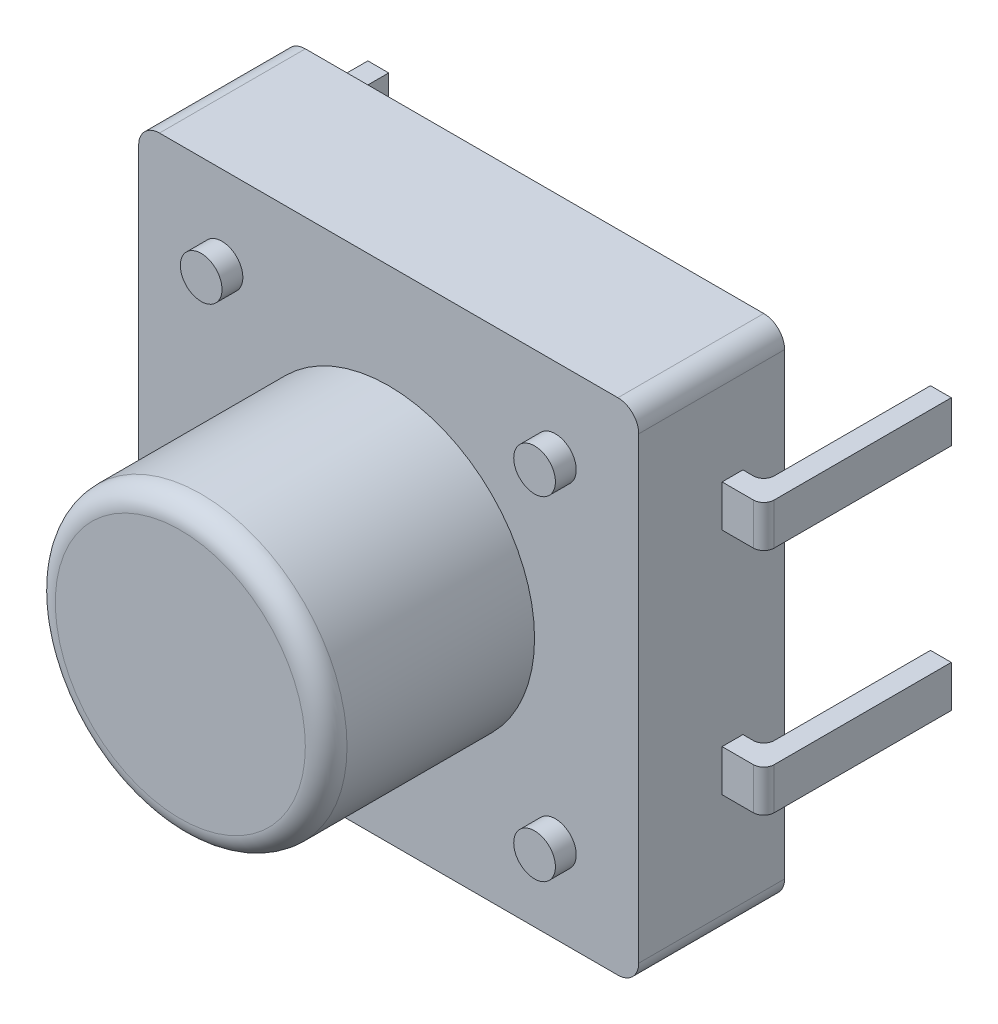
SolidWorks part; units mm, degrees
ref_plane "Ön Düzlem" through (0, 0, 0) normal (0, 0, 1) x (1, 0, 0)
ref_plane "Üst Düzlem" through (0, 0, 0) normal (0, 1, 0) x (1, 0, 0)
ref_plane "Sağ Düzlem" through (0, 0, 0) normal (1, 0, 0) x (0, 0, -1)
sketch "Çizim1" plane through (0, 0, 0) normal (0, 0, 1) x (1, 0, 0)
  line L1 (0.5, 0) -> (11.5, 0)
  line L2 (0, 0.5) -> (0, 11.5)
  line L3 (0.5, 12) -> (11.5, 12)
  line L4 (12, 0.5) -> (12, 11.5)
  arc A0 (0.5, 0) -> (0, 0.5) centre (0.5, 0.5) cw
  arc A1 (12, 0.5) -> (11.5, 0) centre (11.5, 0.5) cw
  arc A2 (12, 11.5) -> (11.5, 12) centre (11.5, 11.5) ccw
  arc A3 (0, 11.5) -> (0.5, 12) centre (0.5, 11.5) cw
  point P7 (0, 0)
  point P10 (12, 0)
  point P13 (12, 12)
  point P16 (0, 12)
  dimension "D3" = 0.5
  dimension "D1" = 12
  dimension "D2" = 12
extrude "Yükseklik-Ekstrüzyon1" add sketch "Çizim1" along normal blind 3.5
sketch "Çizim2" plane through (0, 0, 3.5) normal (0, 0, 1) x (1, 0, 0)
  line L0 (11.8536, 11.8536) -> (0.1464, 0.1464) construction
  line L1 (0.1464, 11.8536) -> (11.8536, 0.1464) construction
  arc A0 (12, 11.5) -> (11.5, 12) centre (11.5, 11.5) ccw construction
  arc A1 (0, 0.5) -> (0.5, 0) centre (0.5, 0.5) ccw construction
  arc A2 (0.5, 12) -> (0, 11.5) centre (0.5, 11.5) ccw construction
  arc A3 (11.5, 0) -> (12, 0.5) centre (11.5, 0.5) ccw construction
  circle A4 centre (6, 6) radius 3.5
  circle A5 centre (10, 10) radius 0.5
  circle A6 centre (2, 10) radius 0.5
  circle A7 centre (2, 2) radius 0.5
  circle A8 centre (10, 2) radius 0.5
  dimension "D1" = 7
  dimension "D2" = 1
  dimension "D3" = 8
extrude "Yükseklik-Ekstrüzyon2" add sketch "Çizim2" along normal blind 0.5
sketch "Çizim3" plane through (0, 0, 4) normal (0, 0, 1) x (1, 0, 0)
  circle A1 centre (6, 6) radius 3.5
  circle A2 centre (6, 6) radius 3.5
  dimension "D1" = 0
extrude "Yükseklik-Ekstrüzyon3" add sketch "Çizim3" along normal blind 4.5
ref_plane "Düzlem1" through (0, 3, 0) normal (0, -1, 0) x (-1, 0, 0)
sketch "Çizim4" plane through (0, 3, 0) normal (0, -1, 0) x (-1, 0, 0)
  line L0 (0, -1) -> (0.25, -1)
  line L1 (0, -3.5) -> (0, 0) construction
  line L2 (0.5, -0.75) -> (0.5, 3)
  line L3 (0.5, 3) -> (1, 3)
  line L4 (1, 3) -> (1, -1.25)
  line L5 (0.75, -1.5) -> (0, -1.5)
  line L6 (0, -1.5) -> (0, -1)
  line L7 (0, 0) -> (-0.5, 0) construction
  line L8 (-6, 0) -> (-6, -3.5) construction
  line L9 (-0.5, 0) -> (-11.5, 0) construction
  line L10 (-0.5, -3.5) -> (-11.5, -3.5) construction
  line L11 (-12, -1.5) -> (-12, -1)
  line L12 (-12.75, -1.5) -> (-12, -1.5)
  line L13 (-13, 3) -> (-13, -1.25)
  line L14 (-12.5, 3) -> (-13, 3)
  line L15 (-12.5, -0.75) -> (-12.5, 3)
  line L16 (-12, -1) -> (-12.25, -1)
  arc A0 (0.5, -0.75) -> (0.25, -1) centre (0.25, -0.75) cw
  arc A1 (1, -1.25) -> (0.75, -1.5) centre (0.75, -1.25) cw
  arc A2 (-13, -1.25) -> (-12.75, -1.5) centre (-12.75, -1.25) ccw
  arc A3 (-12.5, -0.75) -> (-12.25, -1) centre (-12.25, -0.75) ccw
  point P10 (0.125, -1)
  dimension "D6" = 0.25
  dimension "D1" = 1
  dimension "D2" = 0.5
  dimension "D3" = 0.5
  dimension "D4" = 4
  dimension "D5" = 0.5
extrude "Yükseklik-Ekstrüzyon4" add sketch "Çizim4" against normal blind 1
ref_plane "Düzlem2" through (0, 8.5, 0) normal (0, 1, 0) x (1, 0, 0)
sketch "Çizim6" plane through (0, 8.5, 0) normal (0, 1, 0) x (1, 0, 0)
  line L6 (13, -1.25) -> (13, 3)
  line L7 (13, 3) -> (12.5, 3)
  line L8 (12.5, 3) -> (12.5, -0.75)
  line L9 (12.25, -1) -> (12, -1)
  line L10 (12, -1) -> (12, -1.5)
  line L11 (12, -1.5) -> (12.75, -1.5)
  line L12 (13, -1.25) -> (13, 3)
  line L13 (13, 3) -> (12.5, 3)
  line L14 (12.5, 3) -> (12.5, -0.75)
  line L15 (12.25, -1) -> (12, -1)
  line L16 (12, -1) -> (12, -1.5)
  line L17 (12, -1.5) -> (12.75, -1.5)
  line L18 (0, -1.5) -> (0, -1)
  line L19 (0, -1) -> (-0.25, -1)
  line L20 (-0.5, -0.75) -> (-0.5, 3)
  line L21 (-0.5, 3) -> (-1, 3)
  line L22 (-1, 3) -> (-1, -1.25)
  line L23 (-0.75, -1.5) -> (0, -1.5)
  line L24 (0, -1.5) -> (0, -1)
  line L25 (0, -1) -> (-0.25, -1)
  line L26 (-0.5, -0.75) -> (-0.5, 3)
  line L27 (-0.5, 3) -> (-1, 3)
  line L28 (-1, 3) -> (-1, -1.25)
  line L29 (-0.75, -1.5) -> (0, -1.5)
  arc A2 (12.75, -1.5) -> (13, -1.25) centre (12.75, -1.25) ccw
  arc A3 (12.25, -1) -> (12.5, -0.75) centre (12.25, -0.75) ccw
  arc A4 (12.75, -1.5) -> (13, -1.25) centre (12.75, -1.25) ccw
  arc A5 (12.25, -1) -> (12.5, -0.75) centre (12.25, -0.75) ccw
  arc A6 (-0.5, -0.75) -> (-0.25, -1) centre (-0.25, -0.75) ccw
  arc A7 (-1, -1.25) -> (-0.75, -1.5) centre (-0.75, -1.25) ccw
  arc A8 (-0.5, -0.75) -> (-0.25, -1) centre (-0.25, -0.75) ccw
  arc A9 (-1, -1.25) -> (-0.75, -1.5) centre (-0.75, -1.25) ccw
  dimension "D1" = 0
  dimension "D2" = 0
extrude "Yükseklik-Ekstrüzyon5" add sketch "Çizim6" along normal blind 1
fillet "Radyus1" radius 0.5 1 edges at (9.5, 6, 8.5)
